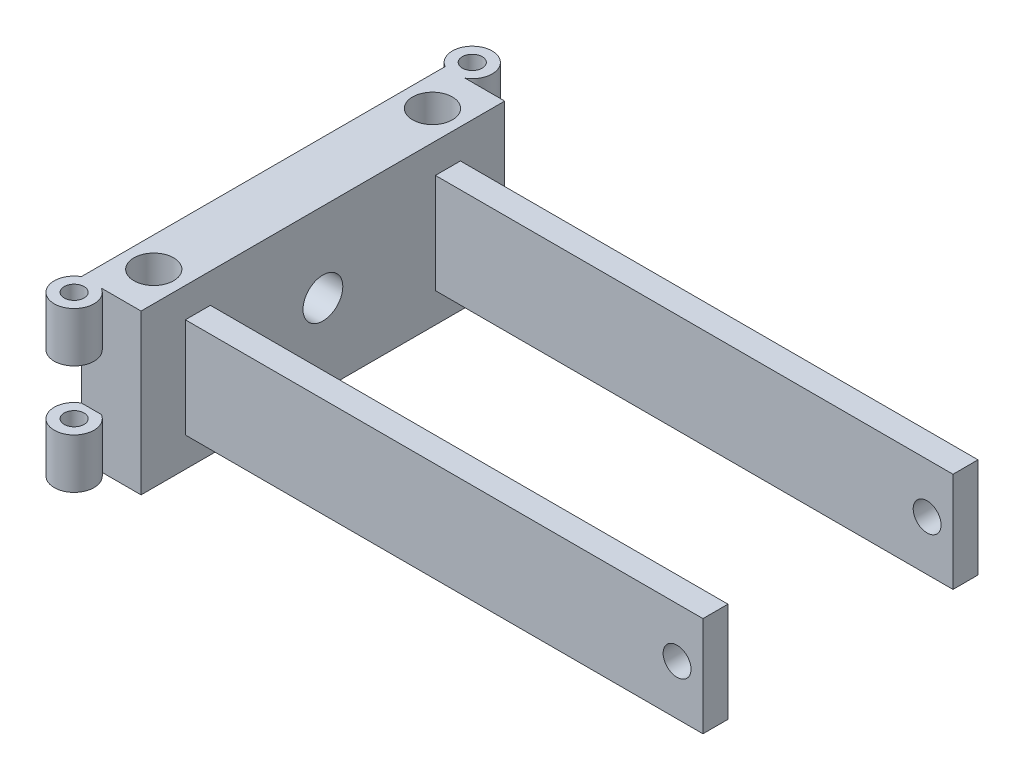
SolidWorks part; units mm, degrees
material "1023 Carbon Steel Sheet (SS)"
ref_plane "Front Plane" through (0, 0, 0) normal (0, 0, 1) x (1, 0, 0)
ref_plane "Top Plane" through (0, 0, 0) normal (0, 1, 0) x (1, 0, 0)
ref_plane "Right Plane" through (0, 0, 0) normal (1, 0, 0) x (0, 0, -1)
sketch "Sketch2" plane through (0, 0, 0) normal (0, 1, 0) x (1, 0, 0)
  line L0 (-5, 45.6699) -> (-2.5, 50) construction
  line L1 (-2.5, 50) -> (0, 45.6699) construction
  line L2 (-5, -45.6699) -> (-5, 45.6699)
  line L3 (-5, -45.6699) -> (-2.5, -50) construction
  line L4 (0, -45.6699) -> (0, 45.6699)
  line L5 (-2.5, -50) -> (0, -45.6699) construction
  arc A0 (-5, 45.6699) -> (0, 45.6699) centre (-2.5, 50) cw
  arc A1 (-5, -45.6699) -> (0, -45.6699) centre (-2.5, -50) ccw
  circle A2 centre (-2.5, 50) radius 2.5
  circle A3 centre (-2.5, -50) radius 2.5
  dimension "D3" = 10
  dimension "D4" = 5
  dimension "D1" = 5
  dimension "D2" = 100
extrude "Boss-Extrude2" add sketch "Sketch2" along normal mid plane 40
sketch "Sketch6" plane through (0, -20, 0) normal (0, -1, 0) x (1, 0, 0)
  line L0 (0, 45.6699) -> (9.9812, 45.6699)
  line L1 (9.9812, 45.6699) -> (9.9812, -45.6699)
  line L2 (9.9812, -45.6699) -> (0, -45.6699)
  line L3 (0, -45.6699) -> (0, 45.6699)
extrude "Boss-Extrude3" add sketch "Sketch6" against normal up to surface (40 mm away) up to face at (-2.5, 20, -47.5)
sketch "Sketch4" plane through (0, 20, 0) normal (0, 1, 0) x (1, 0, 0)
  line L0 (0, 0) -> (-5, 0) construction
  line L1 (-5, 45.6699) -> (-5, -45.6699) construction
  circle A0 centre (2.5, 35) radius 5
  circle A1 centre (2.5, -35) radius 5
  dimension "D2" = 10
  dimension "D1" = 7.5
  dimension "D3" = 35
extrude "Cut-Extrude2" cut sketch "Sketch4" against normal through all both and the other way through all
sketch "Sketch3" plane through (0, 0, 0) normal (1, 0, 0) x (0, 0, -1)
  line L0 (55, -20) -> (55, 20) construction
  line L1 (55, 7.5) -> (45.6699, 7.5)
  line L2 (55, 7.5) -> (55, -7.5)
  line L3 (55, -7.5) -> (45.6699, -7.5)
  line L4 (45.6699, 7.5) -> (45.6699, -7.5)
  line L5 (-55, 20) -> (-55, -20) construction
  line L6 (-55, 7.5) -> (-45.6699, 7.5)
  line L7 (-55, 7.5) -> (-55, -7.5)
  line L8 (-55, -7.5) -> (-45.6699, -7.5)
  line L9 (-45.6699, 7.5) -> (-45.6699, -7.5)
  line L11 (45.6699, 20) -> (45.6699, -20) construction
  circle A0 centre (0, 0) radius 5
  dimension "D1" = 10
  dimension "D3" = 15
extrude "Cut-Extrude1" cut sketch "Sketch3" against normal through all both and the other way through all
sketch "Sketch7" plane through (9.9812, 0, 0) normal (1, 0, 0) x (0, 0, -1)
  line L0 (0, 0) -> (0, 41.631) construction
  line L1 (-34.5421, 12.5329) -> (-28.2613, 12.5329)
  line L2 (-34.5421, 12.5329) -> (-34.5421, -12.5329)
  line L3 (-34.5421, -12.5329) -> (-28.2613, -12.5329)
  line L4 (-28.2613, 12.5329) -> (-28.2613, -12.5329)
  line L5 (34.5421, -12.5329) -> (28.2613, -12.5329)
  line L6 (28.2613, 12.5329) -> (28.2613, -12.5329)
  line L7 (34.5421, 12.5329) -> (28.2613, 12.5329)
  line L8 (34.5421, 12.5329) -> (34.5421, -12.5329)
  point P4 (-28.2613, 0)
extrude "Boss-Extrude4" add sketch "Sketch7" along normal blind 130
sketch "Sketch8" plane through (0, 0, 28.2613) normal (0, 0, -1) x (-1, 0, 0)
  circle A0 centre (-133.4812, 0) radius 3.5
  circle A1 centre (-133.4812, 0) radius 3.5 construction
extrude "Cut-Extrude4" cut sketch "Sketch8" against normal through all and the other way through all
